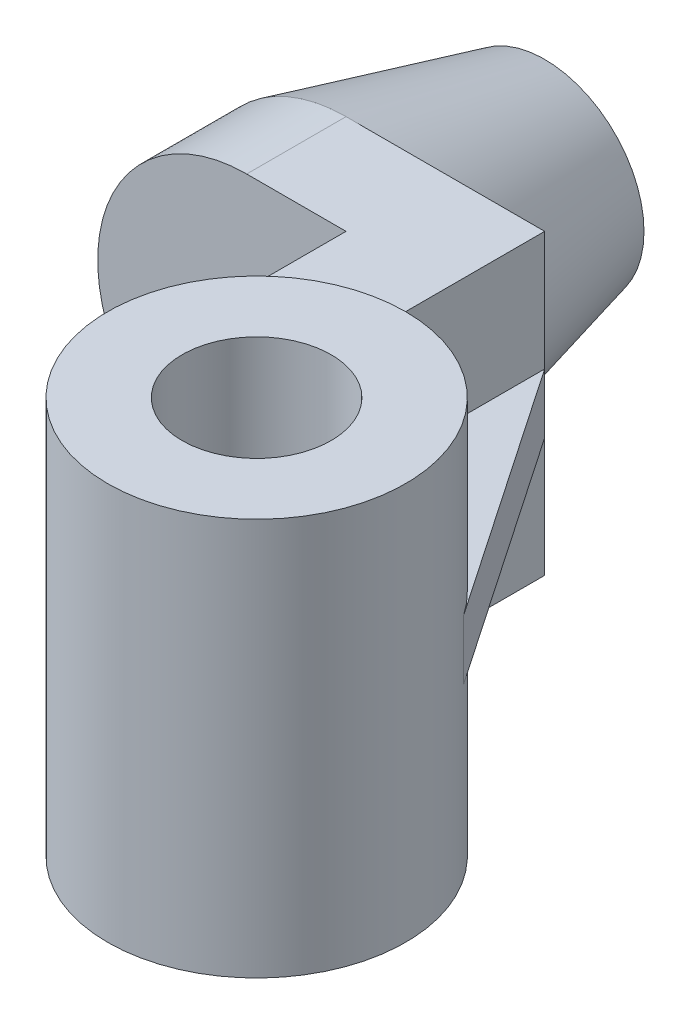
SolidWorks part; units mm, degrees
ref_plane "Front Plane" through (0, 0, 0) normal (0, 0, 1) x (1, 0, 0)
ref_plane "Top Plane" through (0, 0, 0) normal (0, 1, 0) x (1, 0, 0)
ref_plane "Right Plane" through (0, 0, 0) normal (1, 0, 0) x (0, 0, -1)
sketch "Sketch1" plane through (0, 0, 0) normal (0, 1, 0) x (1, 0, 0)
  circle A0 centre (0, 0) radius 15
  circle A1 centre (0, 0) radius 30
extrude "Boss-Extrude2" add sketch "Sketch1" along normal mid plane 80
sketch "Sketch2" plane through (0, 0, 0) normal (0, 1, 0) x (1, 0, 0)
  line L0 (-30, 0) -> (-30, 48)
  line L1 (-30, 48) -> (-50, 48)
  line L2 (-50, 48) -> (-50, 68)
  line L3 (-50, 68) -> (-30, 68)
  line L4 (-30, 68) -> (-10, 68)
  line L5 (-10, 68) -> (-10, 28.2843)
  circle A1 centre (0, 0) radius 30 construction
  arc A2 (-10, 28.2843) -> (-30, 0) centre (0, 0) ccw
  dimension "D1" = 20
  dimension "D2" = 48
  dimension "D3" = 20
extrude "Boss-Extrude8" add sketch "Sketch2" along normal mid plane 60
sketch "Sketch7" plane through (0, 0, -68) normal (0, 0, -1) x (-1, 0, 0)
  line L0 (50, 30) -> (50, -30) construction
  line L1 (50, 30) -> (50, -30)
  arc A0 (50, -30) -> (50, 30) centre (50, 0) ccw
extrude "Boss-Extrude9" add sketch "Sketch7" against normal blind 20
sketch "Sketch9" plane through (0, 0, 0) normal (0, 1, 0) x (1, 0, 0)
  line L0 (-80, 68) -> (-70, 108)
  line L1 (-70, 108) -> (-60, 108)
  line L2 (-60, 108) -> (-60, 68)
  line L4 (-60, 68) -> (-80, 68)
  line L5 (-50, 68) -> (-50, 99.7663) construction
  dimension "D1" = 40
  dimension "D2" = 10
  dimension "D3" = 20
revolve "Revolve2" add sketch "Sketch9" angle 360 about L5
sketch "Sketch10" plane through (0, 0, 0) normal (0, 1, 0) x (1, 0, 0)
  line L0 (-10, 68) -> (24.799, 16.8822)
  circle A0 centre (0, 0) radius 30 construction
rib "Rib1" sketch "Sketch10" sketch "Sketch10" thickness 12 extrusion direction parallel to sketch draft on no parameters "D1"=12
